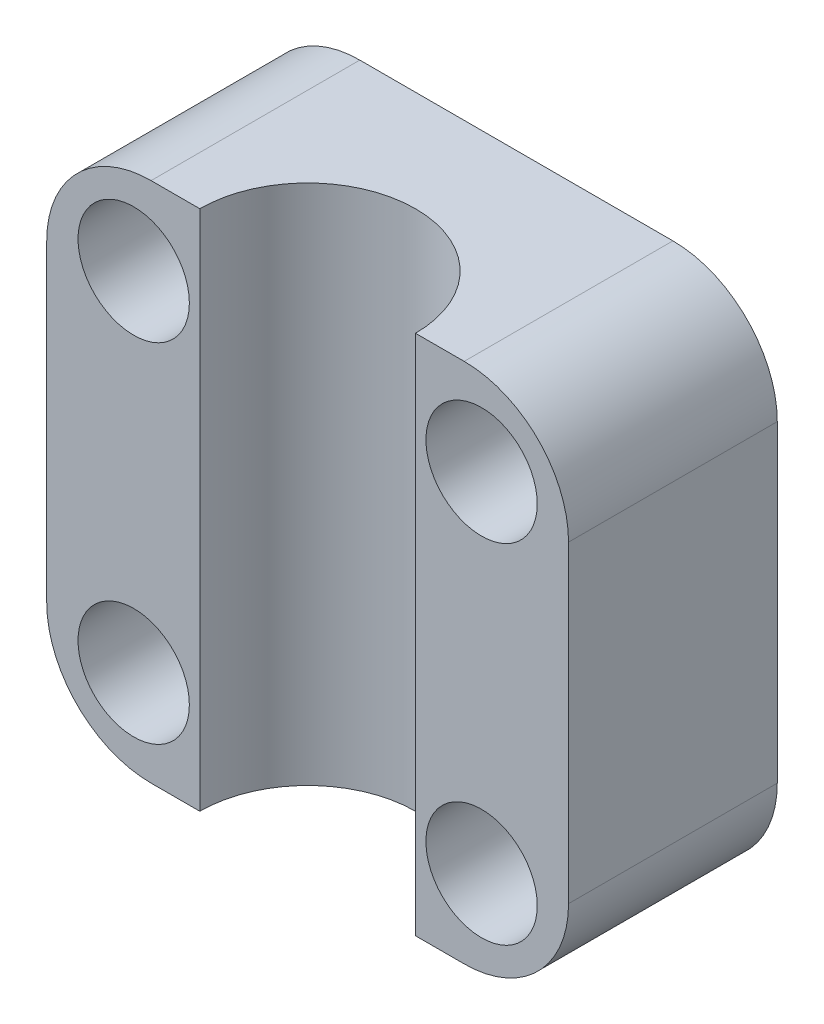
SolidWorks part; units mm, degrees
ref_plane "xy" through (0, 0, 0) normal (0, 0, 1) x (1, 0, 0)
ref_plane "xz" through (0, 0, 0) normal (0, 1, 0) x (1, 0, 0)
ref_plane "yz" through (0, 0, 0) normal (1, 0, 0) x (0, 0, -1)
sketch "Skizze1" plane through (0, 0, 0) normal (0, 0, 1) x (1, 0, 0)
  line L0 (0, 0) -> (-27.5, -27.5) construction
  line L1 (-7.5, 7.5) -> (7.5, 7.5)
  line L2 (-7.5, 7.5) -> (-7.5, -7.5)
  line L3 (-7.5, -7.5) -> (7.5, -7.5)
  line L4 (7.5, 7.5) -> (7.5, -7.5)
  line L5 (-7.5, -7.5) -> (-27.5, -7.5) construction
  line L6 (-7.5, -7.5) -> (-7.5, -27.5) construction
  line L7 (-7.5, -27.5) -> (-27.5, -27.5) construction
  line L8 (-27.5, -7.5) -> (-27.5, -27.5) construction
  line L9 (-27.5, -7.5) -> (-22.5, -7.5) construction
  line L10 (-27.5, -7.5) -> (-27.5, 7.5) construction
  line L11 (-27.5, 7.5) -> (-22.5, 7.5) construction
  line L12 (-22.5, -7.5) -> (-22.5, 7.5) construction
  line L13 (-27.5, 3) -> (28.047, 3) construction
  line L14 (-27.5, 3) -> (-27.5, -3) construction
  line L15 (-27.5, -3) -> (28.047, -3) construction
  line L16 (28.047, 3) -> (28.047, -3) construction
  line L17 (-7.5, -7.5) -> (12.5, -7.5) construction
  line L18 (12.5, -7.5) -> (12.5, -27.5) construction
  line L19 (12.5, -27.5) -> (-7.5, -27.5) construction
  line L20 (12.5, -17.5) -> (14.5, -17.5) construction
  line L21 (14.5, -10) -> (19.5, -10) construction
  line L22 (14.5, -10) -> (14.5, -25) construction
  line L23 (14.5, -25) -> (19.5, -25) construction
  line L24 (19.5, -10) -> (19.5, -25) construction
  line L26 (-5, 5) -> (5, 5) construction
  line L27 (-5, 5) -> (-5, -5) construction
  line L28 (-5, -5) -> (5, -5) construction
  line L29 (5, 5) -> (5, -5) construction
  circle A0 centre (5, 5) radius 1.6
  circle A1 centre (-5, 5) radius 1.6
  circle A2 centre (-5, -5) radius 1.6
  circle A3 centre (5, -5) radius 1.6
  point P4 (0, -7.5)
  point P6 (7.5, 0)
  point P18 (-27.5, 0)
  point P28 (17, -10)
  point P33 (5, 0)
  point P34 (0, -5)
  dimension "D1" = 3.2
  dimension "D2" = 20
  dimension "D3" = 5
  dimension "D4" = 15
  dimension "D5" = 6
  dimension "D6" = 2
  dimension "D7" = 10
  dimension "D8" = 15
extrude "Aufsatz-Linear austragen1" add sketch "Skizze1" against normal blind 6
sketch "Skizze2" plane through (0, 0, 0) normal (0, 1, 0) x (1, 0, 0)
  circle A0 centre (0, 0) radius 3.1
  dimension "D2" = 6.2
extrude "Schnitt-Linear austragen1" cut sketch "Skizze2" along normal through all and the other way through all
fillet "Verrundung1" radius 3 4 edges at (-7.5, 7.5, -3) (7.5, 7.5, -3) (7.5, -7.5, -3) (-7.5, -7.5, -3)
